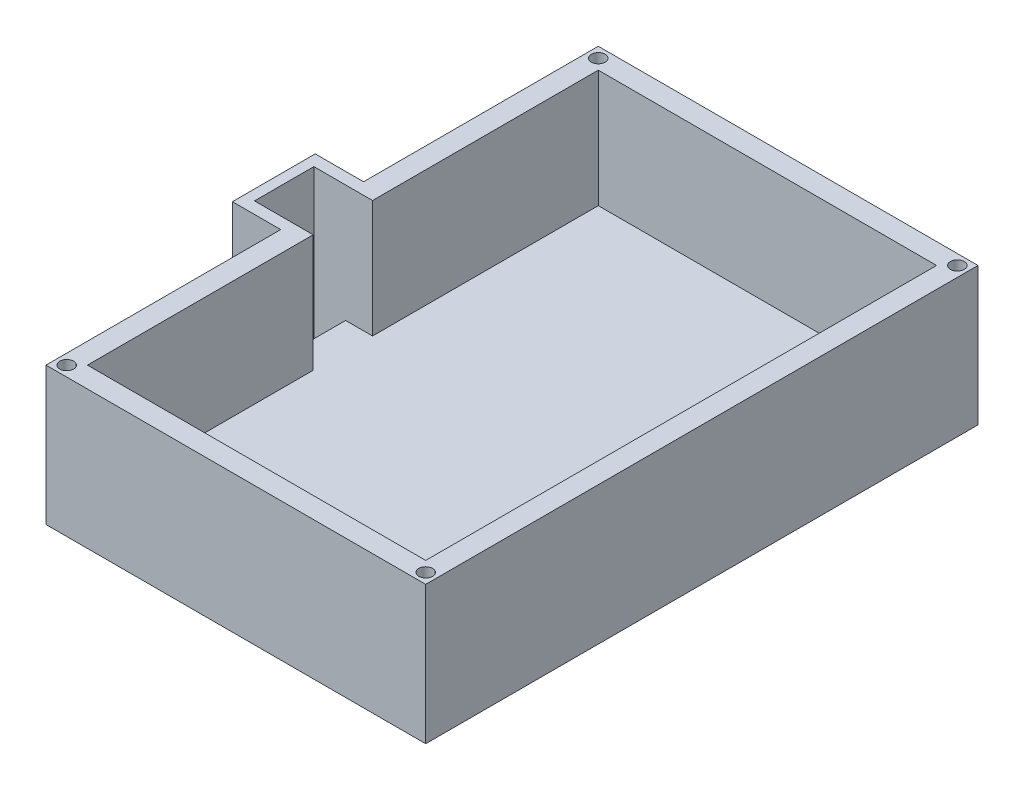
SolidWorks part; units mm, degrees
ref_plane "Front Plane" through (0, 0, 0) normal (0, 0, 1) x (1, 0, 0)
ref_plane "Top Plane" through (0, 0, 0) normal (0, 1, 0) x (1, 0, 0)
ref_plane "Right Plane" through (0, 0, 0) normal (1, 0, 0) x (0, 0, -1)
sketch "Sketch1" plane through (0, 0, 0) normal (0, 1, 0) x (1, 0, 0)
  line L1 (-27.5, 40) -> (27.5, 40)
  line L2 (-27.5, 40) -> (-27.5, -40)
  line L3 (-27.5, -40) -> (27.5, -40)
  line L4 (27.5, 40) -> (27.5, -40)
  line L5 (-27.5, 40) -> (27.5, -40) construction
  line L6 (-27.5, -40) -> (27.5, 40) construction
  point P0 (0, 0)
  dimension "D1" = 55
  dimension "D2" = 80
extrude "Boss-Extrude1" add sketch "Sketch1" along normal blind 20 contours L2 L1 L4 L3
sketch "Sketch2" plane through (0, 20, 0) normal (0, 1, 0) x (1, 0, 0)
  line L1 (-24.5, -37) -> (24.5, -37)
  line L2 (-24.5, -37) -> (-24.5, 37)
  line L3 (-24.5, 37) -> (24.5, 37)
  line L4 (24.5, -37) -> (24.5, 37)
  line L5 (-24.5, -37) -> (24.5, 37) construction
  line L6 (-24.5, 37) -> (24.5, -37) construction
  point P0 (0, 0)
  dimension "D1" = 74
  dimension "D2" = 49
extrude "Cut-Extrude1" cut sketch "Sketch2" against normal blind 17
sketch "Sketch4" plane through (0, 20, 0) normal (0, 1, 0) x (1, 0, 0)
  line L1 (-27.5, 40) -> (-27.5, -40) construction
  line L3 (-43.5, 6) -> (-27.5, 6)
  line L4 (-43.5, 6) -> (-43.5, -6)
  line L5 (-43.5, -6) -> (-27.5, -6)
  line L6 (-27.5, 6) -> (-27.5, -6)
  line L7 (-43.5, 6) -> (-27.5, -6) construction
  line L8 (-43.5, -6) -> (-27.5, 6) construction
  point P5 (-35.5, 0)
  dimension "D1" = 16
  dimension "D2" = 12
extrude "Boss-Extrude2" add sketch "Sketch4" against normal blind 40
sketch "Sketch5" plane through (-43.5, 0, 0) normal (-1, 0, 0) x (0, 0, 1)
  line L3 (-2.5, -13) -> (2.5, -13)
  line L4 (-2.5, -13) -> (-2.5, -17)
  line L5 (-2.5, -17) -> (2.5, -17)
  line L6 (2.5, -13) -> (2.5, -17)
  line L7 (-2.5, -13) -> (2.5, -17) construction
  line L8 (-2.5, -17) -> (2.5, -13) construction
  dimension "D2" = 4
  dimension "D3" = 5
sketch "Sketch6" plane through (0, 20, 0) normal (0, 1, 0) x (1, 0, 0)
  line L0 (-43.5, 2.5) -> (-43.5, -2.5) construction
  line L1 (-52.5, 10) -> (-34.5, 10)
  line L2 (-52.5, 10) -> (-52.5, -10)
  line L3 (-52.5, -10) -> (-34.5, -10)
  line L4 (-34.5, 10) -> (-34.5, -10)
  line L5 (-52.5, 10) -> (-34.5, -10) construction
  line L6 (-52.5, -10) -> (-34.5, 10) construction
  point P0 (-43.5, 0)
  dimension "D1" = 18
  dimension "D2" = 20
extrude "Cut-Extrude2" cut sketch "Sketch6" against normal blind 43
extrude "Cut-Extrude3" cut sketch "Sketch5" against normal blind 15
sketch "Sketch7" plane through (0, 20, 0) normal (0, 1, 0) x (1, 0, 0)
  line L0 (-34.5, -6) -> (-34.5, 6) construction
  line L4 (-33, 4.3) -> (-28.4, 4.3)
  line L5 (-33, 4.3) -> (-33, -4.3)
  line L6 (-33, -4.3) -> (-28.4, -4.3)
  line L10 (-28.4, 4.3) -> (-28.4, -4.3)
  line L11 (-33, 4.3) -> (-34.5, 4.3)
  point P6 (-29.2242, 0)
  dimension "D1" = 4.6
  dimension "D2" = 8.6
extrude "Cut-Extrude6" cut sketch "Sketch7" against normal blind 34 contours L10 L4 L5 L6
sketch "Sketch9" plane through (0, 20, 0) normal (0, 1, 0) x (1, 0, 0)
  line L0 (-24.5, 37) -> (-24.5, -37) construction
  line L1 (-28.4, 4.3) -> (-24.5, 4.3)
  line L2 (-28.4, 4.3) -> (-28.4, -4.3)
  line L3 (-28.4, -4.3) -> (-24.5, -4.3)
  line L4 (-24.5, 4.3) -> (-24.5, -4.3)
extrude "Cut-Extrude7" cut sketch "Sketch9" against normal blind 17
sketch "Sketch10" plane through (0, 20, 0) normal (0, 1, 0) x (1, 0, 0)
  line L0 (-27.5, 40) -> (-24.5, 37)
  line L1 (27.5, 40) -> (24.5, 37)
  line L2 (-24.5, -37) -> (-27.5, -40)
  line L3 (27.5, -40) -> (24.5, -37)
  circle A0 centre (-26, -38.5) radius 1
  circle A1 centre (26, -38.5) radius 1
  circle A2 centre (26, 38.5) radius 1
  circle A3 centre (-26, 38.5) radius 1
  dimension "D1" = 2
extrude "Cut-Extrude8" cut sketch "Sketch10" against normal blind 3 contours A3 | A2 | A1 | A0
sketch "Sketch13" plane through (0, 0, 0) normal (0, -1, 0) x (-1, 0, 0)
  line L0 (0, 0) -> (0, -40) construction
  line L1 (27.5, -40) -> (-27.5, -40) construction
  line L2 (0, -40) -> (0, 0) construction
  line L3 (0, 0) -> (0, 40) construction
  line L4 (27.5, 40) -> (-27.5, 40) construction
  line L5 (0, 0) -> (-27.5, 0)
  line L6 (-27.5, 40) -> (-27.5, -40) construction
  line L7 (-27.5, 0) -> (27.5, 0)
  line L8 (27.5, 6) -> (27.5, -6) construction
  line L9 (0, -20) -> (-27.5, -20) construction
  line L10 (-27.5, -20) -> (27.5, -20) construction
  line L11 (27.5, -6) -> (27.5, -40) construction
  line L12 (0, 20) -> (-27.5, 20) construction
  line L13 (-27.5, 20) -> (27.5, 20) construction
  line L14 (27.5, 40) -> (27.5, 6) construction
  line L16 (-3.5, 29) -> (3.5, 29)
  line L17 (-3.5, 29) -> (-3.5, 11)
  line L18 (-3.5, 11) -> (3.5, 11)
  line L19 (3.5, 29) -> (3.5, 11)
  line L20 (-3.5, 29) -> (3.5, 11) construction
  line L21 (-3.5, 11) -> (3.5, 29) construction
  line L22 (-3.5, -11) -> (3.5, -11)
  line L23 (-3.5, -11) -> (-3.5, -29)
  line L24 (-3.5, -29) -> (3.5, -29)
  line L25 (3.5, -11) -> (3.5, -29)
  line L26 (-3.5, -11) -> (3.5, -29) construction
  line L27 (-3.5, -29) -> (3.5, -11) construction
  point P32 (0, 0)
  point P33 (0, 0)
  dimension "D1" = 18
  dimension "D2" = 18
  dimension "D3" = 7
  dimension "D4" = 7
extrude "Boss-Extrude3" add sketch "Sketch13" along normal blind 7 contours L25 L24 L23 L22 | L19 L18 L17 L16
sketch "Sketch14" plane through (-3.5, 0, 0) normal (-1, 0, 0) x (0, 0, 1)
  line L10 (20, -3.5) -> (29, -3.5)
  line L11 (29, -7) -> (29, 0) construction
  line L15 (-26, -4.5) -> (-14, -4.5)
  line L16 (-26, -4.5) -> (-26, -2.5)
  line L17 (-26, -2.5) -> (-14, -2.5)
  line L18 (-14, -4.5) -> (-14, -2.5)
  line L19 (-26, -4.5) -> (-14, -2.5) construction
  line L20 (-26, -2.5) -> (-14, -4.5) construction
  line L21 (14, -4.5) -> (26, -4.5)
  line L22 (14, -4.5) -> (14, -2.5)
  line L23 (14, -2.5) -> (26, -2.5)
  line L24 (26, -4.5) -> (26, -2.5)
  line L25 (14, -4.5) -> (26, -2.5) construction
  line L26 (14, -2.5) -> (26, -4.5) construction
  point P0 (0, 0)
  point P26 (-20, -3.5)
  point P34 (0, 0)
  point P35 (0, 0)
  point P36 (0, 0)
  dimension "D1" = 2
  dimension "D2" = 12
  dimension "D3" = 12
  dimension "D4" = 2
extrude "Cut-Extrude9" cut sketch "Sketch14" against normal blind 9 and the other way blind 3
